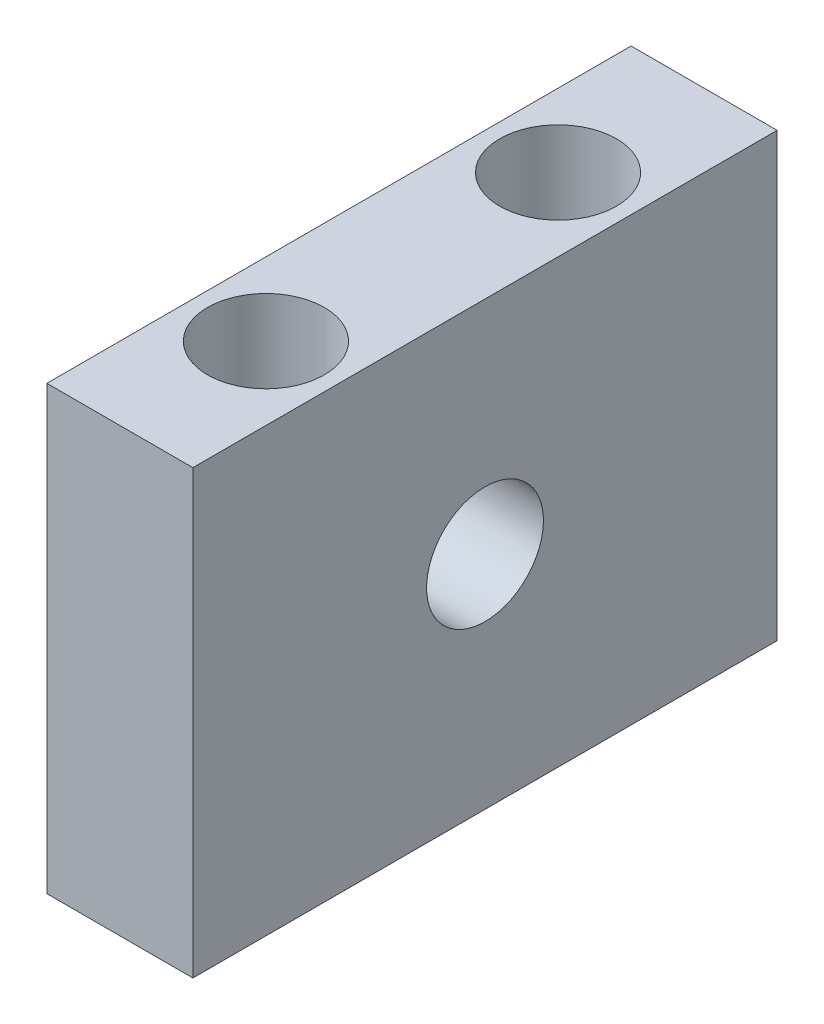
SolidWorks part; units mm, degrees
ref_plane "Alzado" through (0, 0, 0) normal (0, 0, 1) x (1, 0, 0)
ref_plane "Planta" through (0, 0, 0) normal (0, 1, 0) x (1, 0, 0)
ref_plane "Vista lateral" through (0, 0, 0) normal (1, 0, 0) x (0, 0, -1)
sketch "Croquis1" plane through (0, 0, 0) normal (0, 1, 0) x (1, 0, 0)
  line L0 (-5, 20) -> (5, 20)
  line L1 (-5, 20) -> (-5, -20)
  line L2 (-5, -20) -> (5, -20)
  line L3 (5, 20) -> (5, -20)
  line L4 (-5, 20) -> (5, -20) construction
  line L5 (-5, -20) -> (5, 20) construction
  point P0 (0, 0)
extrude "Saliente-Extruir1" add sketch "Croquis1" along normal blind 30.26
sketch "Croquis2" plane through (0, 0, 0) normal (0, 1, 0) x (1, 0, 0)
  line L0 (0, 0) -> (0, -10) construction
  line L1 (0, 0) -> (0, 10) construction
  circle A0 centre (0, -10) radius 4
  circle A1 centre (0, 10) radius 4
  dimension "D1" = 8
  dimension "D2" = 8
  dimension "D3" = 20
extrude "Cortar-Extruir1" cut sketch "Croquis2" along normal blind 30.26
sketch "Croquis5" plane through (0, 0, 0) normal (1, 0, 0) x (0, 0, -1)
  line L0 (-20, 15.13) -> (0, 15.13) construction
  line L1 (-20, 30.26) -> (-20, 0) construction
  circle A0 centre (0, 15.13) radius 4
  dimension "D1" = 8
extrude "Cortar-Extruir2" cut sketch "Croquis5" against normal mid plane 30.26
